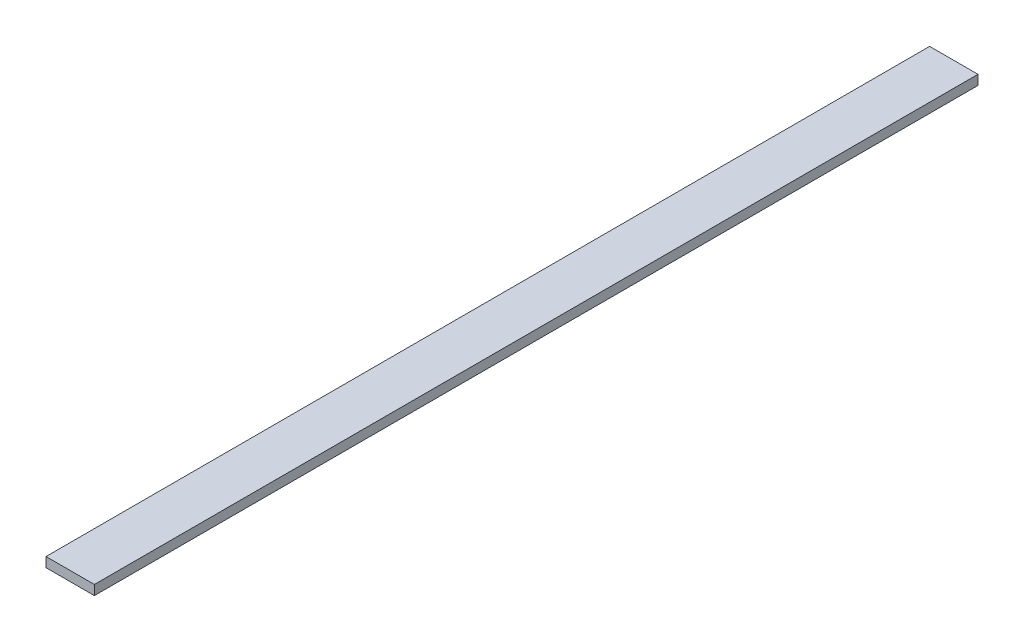
SolidWorks part; units mm, degrees
ref_plane "Front Plane" through (0, 0, 0) normal (0, 0, 1) x (1, 0, 0)
ref_plane "Top Plane" through (0, 0, 0) normal (0, 1, 0) x (1, 0, 0)
ref_plane "Right Plane" through (0, 0, 0) normal (1, 0, 0) x (0, 0, -1)
sketch "Sketch1" plane through (0, 0, 0) normal (0, 1, 0) x (1, 0, 0)
  line L1 (0, 91.3239) -> (-10, 91.3239)
  line L2 (0, 91.3239) -> (0, -91.3239)
  line L3 (-10, 91.3239) -> (-10, -91.3239)
  line L4 (0, -91.3239) -> (-10, -91.3239)
extrude "Boss-Extrude1" add sketch "Sketch1" along normal blind 2
